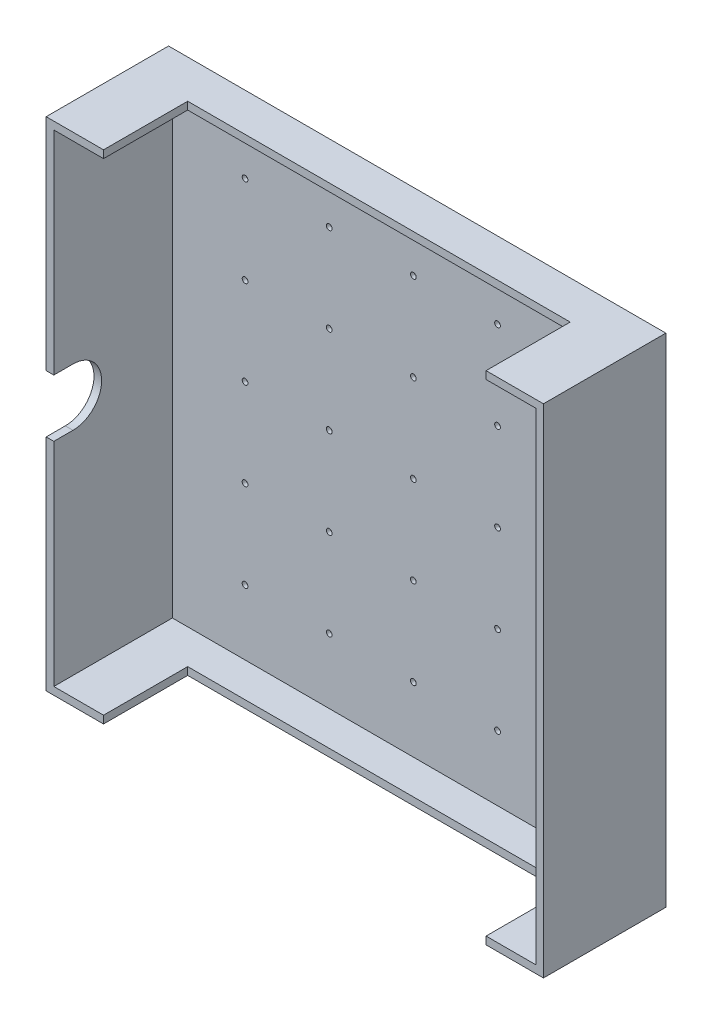
SolidWorks part; units mm, degrees
ref_plane "Plan de face" through (0, 0, 0) normal (0, 0, 1) x (1, 0, 0)
ref_plane "Plan de dessus" through (0, 0, 0) normal (0, 1, 0) x (1, 0, 0)
ref_plane "Plan de droite" through (0, 0, 0) normal (1, 0, 0) x (0, 0, -1)
sketch "Esquisse1" plane through (0, 0, 0) normal (0, 0, 1) x (1, 0, 0)
  line L1 (0, 130) -> (130, 130)
  line L2 (0, 130) -> (0, 0)
  line L3 (0, 0) -> (130, 0)
  line L4 (130, 130) -> (130, 0)
extrude "Boss.-Extru.1" add sketch "Esquisse1" along normal blind 1
sketch "Esquisse2" plane through (0, 0, 1) normal (0, 0, 1) x (1, 0, 0)
  line L0 (128, 2) -> (128, 128)
  line L1 (2, 2) -> (128, 2)
  line L2 (128, 128) -> (2, 128)
  line L3 (2, 128) -> (2, 2)
  line L4 (0, 130) -> (0, 0)
  line L5 (0, 0) -> (130, 0)
  line L6 (130, 0) -> (130, 130)
  line L7 (130, 130) -> (0, 130)
  line L8 (0, 130) -> (0, 0)
  line L9 (0, 0) -> (130, 0)
  line L10 (130, 0) -> (130, 130)
  line L11 (130, 130) -> (0, 130)
  dimension "D2" = 2
  dimension "D3" = 2
  dimension "D4" = 2
  dimension "D5" = 2
  dimension "D1" = 0
extrude "Boss.-Extru.2" add sketch "Esquisse2" along normal blind 31
sketch "Esquisse4" plane through (0, 0, 1) normal (0, 0, 1) x (1, 0, 0)
  line L0 (65, 130) -> (65, 0) construction
  line L1 (130, 130) -> (0, 130) construction
  line L2 (0, 0) -> (130, 0) construction
  circle A0 centre (65, 65) radius 16.1171 construction
sketch "Esquisse3" plane through (0, 0, 0) normal (-1, 0, 0) x (0, 0, 1)
  line L1 (1, 130) -> (1, 0) construction
  line L5 (32, 72.5) -> (32, 57.5)
  line L6 (32, 65) -> (27, 65) construction
  line L7 (32, 57.5) -> (27, 57.5)
  line L8 (32, 72.5) -> (27, 72.5)
  line L9 (32, 130) -> (32, 0) construction
  arc A2 (32, 57.5) -> (32, 72.5) centre (32, 65) ccw construction
  arc A3 (27, 72.5) -> (27, 57.5) centre (27, 65) ccw
  point P5 (1, 65)
  point P16 (29.5, 65)
  line M5 (32, 0) -> (32, 130)
  dimension "D1" = 7.5
  dimension "D2" = 5
extrude "Enlèv. mat.-Extru.1" cut sketch "Esquisse3" against normal up to surface (2 mm away) contours L8 A3 L7 M5 up to face at (2, 65, 16.5)
sketch "Esquisse5" plane through (0, 0, 0) normal (0, 0, -1) x (-1, 0, 0)
  circle A0 centre (-65, 65) radius 2 construction
  circle A1 centre (-43, 65) radius 2 construction
  circle A2 centre (-21, 65) radius 2 construction
  circle A3 centre (-43, 42) radius 2 construction
  circle A4 centre (-21, 42) radius 2 construction
  circle A5 centre (-43, 19) radius 2 construction
  circle A6 centre (-21, 19) radius 2 construction
  circle A7 centre (-65, 42) radius 2 construction
  circle A8 centre (-65, 19) radius 2 construction
  circle A9 centre (-109, 65) radius 2 construction
  circle A10 centre (-87, 65) radius 2 construction
  circle A11 centre (-87, 42) radius 2 construction
  circle A12 centre (-87, 19) radius 2 construction
  circle A13 centre (-109, 42) radius 2 construction
  circle A14 centre (-109, 19) radius 2 construction
  circle A15 centre (-65, 111) radius 2 construction
  circle A16 centre (-43, 111) radius 2 construction
  circle A17 centre (-21, 111) radius 2 construction
  circle A18 centre (-43, 88) radius 2 construction
  circle A19 centre (-21, 88) radius 2 construction
  circle A20 centre (-65, 88) radius 2 construction
  circle A21 centre (-109, 111) radius 2 construction
  circle A22 centre (-87, 111) radius 2 construction
  circle A23 centre (-87, 88) radius 2 construction
  circle A24 centre (-109, 88) radius 2 construction
  circle A25 centre (-109, 111) radius 0.75
  circle A26 centre (-87, 111) radius 0.75
  circle A27 centre (-65, 111) radius 0.75
  circle A28 centre (-43, 111) radius 0.75
  circle A29 centre (-21, 111) radius 0.75
  circle A30 centre (-109, 88) radius 0.75
  circle A31 centre (-87, 88) radius 0.75
  circle A32 centre (-65, 88) radius 0.75
  circle A33 centre (-43, 88) radius 0.75
  circle A34 centre (-21, 88) radius 0.75
  circle A35 centre (-109, 65) radius 0.75
  circle A36 centre (-87, 65) radius 0.75
  circle A37 centre (-65, 65) radius 0.75
  circle A38 centre (-43, 65) radius 0.75
  circle A39 centre (-21, 65) radius 0.75
  circle A40 centre (-109, 42) radius 0.75
  circle A41 centre (-87, 42) radius 0.75
  circle A42 centre (-65, 42) radius 0.75
  circle A43 centre (-43, 42) radius 0.75
  circle A44 centre (-21, 42) radius 0.75
  circle A45 centre (-109, 19) radius 0.75
  circle A46 centre (-87, 19) radius 0.75
  circle A47 centre (-65, 19) radius 0.75
  circle A48 centre (-43, 19) radius 0.75
  circle A49 centre (-21, 19) radius 0.75
  dimension "D1" = 3
  dimension "D5" = 5
  dimension "D2" = 3
  dimension "D3" = 2
  dimension "D4" = 2
sketch "Esquisse6" plane through (0, 130, 0) normal (0, 1, 0) x (1, 0, 0)
  line L0 (130, -32) -> (0, -32) construction
  line L1 (115, -32) -> (15, -32)
  line L2 (115, -32) -> (115, -10)
  line L3 (115, -10) -> (15, -10)
  line L4 (15, -32) -> (15, -10)
  line L5 (0, -32) -> (0, 0) construction
  line L6 (130, -32) -> (130, 0) construction
  line L8 (130, 0) -> (0, 0) construction
  dimension "D1" = 15
  dimension "D2" = 15
  dimension "D3" = 10
extrude "Enlèv. mat.-Extru.2" cut sketch "Esquisse6" against normal through all
extrude "Enlèv. mat.-Extru.3" cut sketch "Esquisse5" against normal up to surface (1 mm away) up to face at (65, 65, 1)
